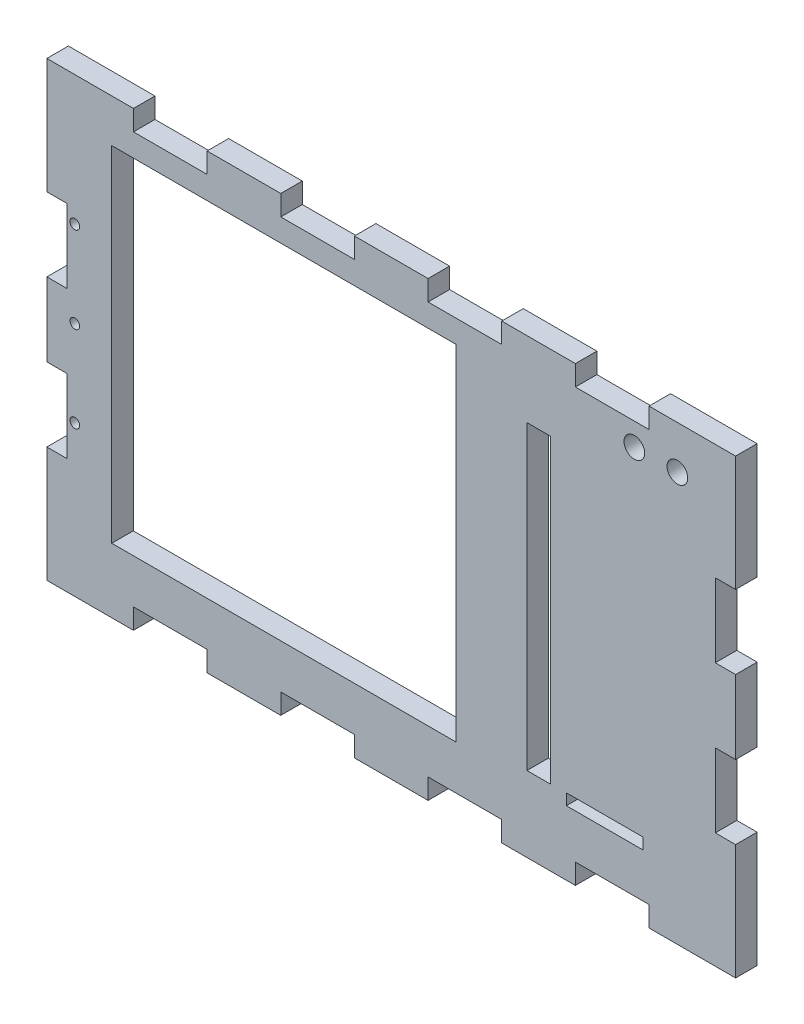
SolidWorks part; units mm, degrees
ref_plane "Front Plane" through (0, 0, 0) normal (0, 0, 1) x (1, 0, 0)
ref_plane "Top Plane" through (0, 0, 0) normal (0, 1, 0) x (1, 0, 0)
ref_plane "Right Plane" through (0, 0, 0) normal (1, 0, 0) x (0, 0, -1)
sketch "Sketch3" plane through (0, 0, 0) normal (0, 0, 1) x (1, 0, 0)
  line L162 (0, 77.5398) -> (0, 55.8102)
  line L163 (0, 55.8102) -> (5.9944, 55.8102)
  line L164 (5.9944, 55.8102) -> (5.9944, 34.0804)
  line L165 (5.9944, 34.0804) -> (0, 34.0804)
  line L166 (0, 34.0804) -> (0, 12.3508)
  line L167 (0, 12.3508) -> (0, 0)
  line L168 (0, 0) -> (25.5461, 0)
  line L169 (25.5461, 0) -> (25.5461, 5.9944)
  line L170 (25.5461, 5.9944) -> (47.2757, 5.9944)
  line L171 (47.2757, 5.9944) -> (47.2757, 0)
  line L172 (47.2757, 0) -> (69.0054, 0)
  line L173 (69.0054, 0) -> (69.0054, 5.9944)
  line L174 (69.0054, 5.9944) -> (90.7352, 5.9944)
  line L175 (90.7352, 5.9944) -> (90.7352, 0)
  line L176 (90.7352, 0) -> (112.4648, 0)
  line L177 (112.4648, 0) -> (112.4648, 5.9944)
  line L178 (112.4648, 5.9944) -> (134.1945, 5.9944)
  line L179 (134.1945, 5.9944) -> (134.1945, 0)
  line L180 (134.1945, 0) -> (155.9242, 0)
  line L181 (155.9242, 0) -> (155.9242, 5.9944)
  line L182 (155.9242, 5.9944) -> (177.6539, 5.9944)
  line L183 (177.6539, 5.9944) -> (177.6539, 0)
  line L184 (177.6539, 0) -> (203.2, 0)
  line L185 (203.2, 0) -> (203.2, 34.0804)
  line L186 (203.2, 34.0804) -> (197.2056, 34.0804)
  line L187 (197.2056, 34.0804) -> (197.2056, 55.8102)
  line L188 (197.2056, 55.8102) -> (203.2, 55.8102)
  line L189 (203.2, 55.8102) -> (203.2, 77.5398)
  line L190 (203.2, 77.5398) -> (197.2056, 77.5398)
  line L191 (197.2056, 77.5398) -> (197.2056, 99.2695)
  line L192 (197.2056, 99.2695) -> (203.2, 99.2695)
  line L193 (203.2, 99.2695) -> (203.2, 120.9993)
  line L194 (203.2, 120.9993) -> (203.2, 133.35)
  line L195 (203.2, 133.35) -> (177.6539, 133.35)
  line L196 (177.6539, 133.35) -> (177.6539, 127.3556)
  line L197 (177.6539, 127.3556) -> (155.9242, 127.3556)
  line L198 (155.9242, 127.3556) -> (155.9242, 133.35)
  line L199 (155.9242, 133.35) -> (134.1945, 133.35)
  line L200 (134.1945, 133.35) -> (134.1945, 127.3556)
  line L201 (134.1945, 127.3556) -> (112.4648, 127.3556)
  line L202 (112.4648, 127.3556) -> (112.4648, 133.35)
  line L203 (112.4648, 133.35) -> (90.7352, 133.35)
  line L204 (90.7352, 133.35) -> (90.7352, 127.3556)
  line L205 (90.7352, 127.3556) -> (69.0054, 127.3556)
  line L206 (69.0054, 127.3556) -> (69.0054, 133.35)
  line L207 (69.0054, 133.35) -> (47.2757, 133.35)
  line L208 (47.2757, 133.35) -> (47.2757, 127.3556)
  line L209 (47.2757, 127.3556) -> (25.5461, 127.3556)
  line L210 (25.5461, 127.3556) -> (25.5461, 133.35)
  line L211 (25.5461, 133.35) -> (0, 133.35)
  line L212 (0, 133.35) -> (0, 99.2695)
  line L213 (0, 99.2695) -> (5.9944, 99.2695)
  line L214 (5.9944, 99.2695) -> (5.9944, 77.5398)
  line L215 (5.9944, 77.5398) -> (0, 77.5398)
extrude "Boss-Extrude1" add sketch "Sketch3" along normal blind 6.35
sketch "Sketch4" plane through (0, 0, 6.35) normal (0, 0, 1) x (1, 0, 0)
  line L0 (47.2757, 0) -> (69.0054, 0) construction
  line L1 (19.142, 120.65) -> (120.742, 120.65)
  line L2 (19.142, 120.65) -> (19.142, 19.05)
  line L3 (19.142, 19.05) -> (120.742, 19.05)
  line L4 (120.742, 120.65) -> (120.742, 19.05)
  line L5 (-919.1944, 120.65) -> (49080.8056, 120.65) construction
  line L6 (153.254, 22.352) -> (175.86, 22.352)
  line L7 (153.254, 22.352) -> (153.254, 19.05)
  line L8 (153.254, 19.05) -> (175.86, 19.05)
  line L9 (175.86, 22.352) -> (175.86, 19.05)
  circle A0 centre (173.32, 120.65) radius 3.048
  circle A1 centre (186.02, 120.65) radius 3.048
  dimension "D7" = 12.7
  dimension "D8" = 6.096
  dimension "D1" = 101.6
  dimension "D2" = 101.6
  dimension "D3" = 19.05
  dimension "D4" = 22.606
  dimension "D5" = 3.302
  dimension "D6" = 32.512
  dimension "D9" = 52.578
extrude "Cut-Extrude1" cut sketch "Sketch4" against normal through all both and the other way through all contours L4 L1 L2 L3 | A1 L5 | A0 L5 | L5 A0 | L5 A1 | L9 L6 L7 L8
sketch "Sketch5" plane through (0, 0, 0) normal (0, 0, -1) x (-1, 0, 0)
  line L0 (-141.6294, 66.675) -> (-148.5179, 66.675) construction
  line L5 (-148.5179, 111.125) -> (-141.6294, 111.125)
  line L6 (-148.5179, 111.125) -> (-148.5179, 22.225)
  line L7 (-148.5179, 22.225) -> (-141.6294, 22.225)
  line L8 (-141.6294, 111.125) -> (-141.6294, 22.225)
  line L10 (-155.9242, 133.35) -> (-134.1945, 133.35) construction
  line L12 (-134.1945, 0) -> (-155.9242, 0) construction
  line L13 (-145.0594, 133.35) -> (-145.0594, 0) construction
  dimension "D1" = 6.8885
  dimension "D2" = 88.9
  dimension "D3" = 66.675
  dimension "D4" = 3.43
extrude "Cut-Extrude2" cut sketch "Sketch5" against normal up to surface (6.35 mm away) up to face at (69.942, 69.85, 6.35)
sketch "Sketch6" plane through (0, 0, 6.35) normal (0, 0, 1) x (1, 0, 0)
  circle A0 centre (8.25, 95.142) radius 1.4293
  circle A1 centre (8.25, 69.742) radius 1.4293
  circle A2 centre (8.25, 44.342) radius 1.4293
  dimension "D1" = 2.8586
extrude "Cut-Extrude3" cut sketch "Sketch6" against normal blind 13.97
